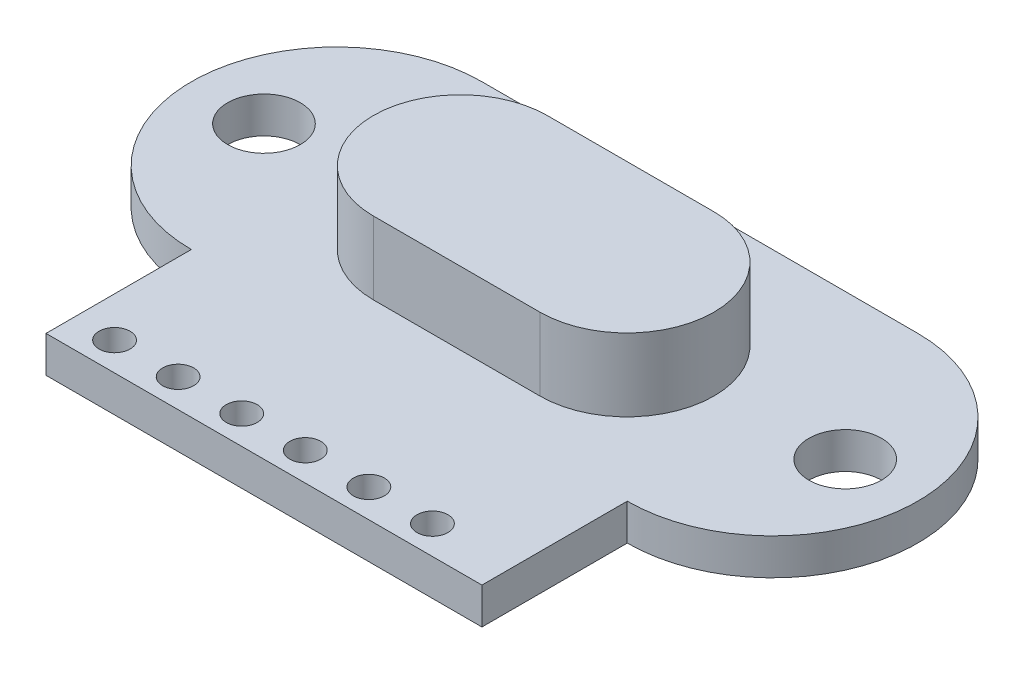
SolidWorks part; units mm, degrees
ref_plane "Front Plane" through (0, 0, 0) normal (0, 0, 1) x (1, 0, 0)
ref_plane "Top Plane" through (0, 0, 0) normal (0, 1, 0) x (1, 0, 0)
ref_plane "Right Plane" through (0, 0, 0) normal (1, 0, 0) x (0, 0, -1)
sketch "Sketch1" plane through (0, 0, 0) normal (0, 1, 0) x (1, 0, 0)
  line L0 (-6, 8) -> (6, 8) construction
  line L1 (-6, 12) -> (6, 12)
  line L2 (-6, 4) -> (6, 4)
  line L3 (0, 8) -> (0, 0) construction
  arc A0 (-6, 12) -> (-6, 4) centre (-6, 8) ccw
  arc A1 (6, 4) -> (6, 12) centre (6, 8) ccw
  point P2 (0, 8)
  dimension "D2" = 20
  dimension "D1" = 12
  dimension "D3" = 8
extrude "Boss-Extrude1" add sketch "Sketch1" along normal blind 1
sketch "Sketch2" plane through (0, 0, 0) normal (0, -1, 0) x (1, 0, 0)
  line L1 (-6, -4) -> (6, -4)
  line L2 (-6, -4) -> (-6, 0)
  line L3 (-6, 0) -> (6, 0)
  line L4 (6, -4) -> (6, 0)
extrude "Boss-Extrude2" add sketch "Sketch2" against normal blind 1
sketch "Sketch3" plane through (0, 1, 0) normal (0, 1, 0) x (1, 0, 0)
  line L0 (-8, 8) -> (8, 8) construction
  line L1 (0, 4) -> (0, 8) construction
  circle A0 centre (8, 8) radius 1
  circle A1 centre (-8, 8) radius 1
  circle A2 centre (-4.8957, 0.7833) radius 0.4268
  circle A8 centre (-3.1457, 0.7833) radius 0.4268
  circle A9 centre (-1.3957, 0.7833) radius 0.4268
  circle A10 centre (0.3543, 0.7833) radius 0.4268
  circle A11 centre (2.1043, 0.7833) radius 0.4268
  circle A12 centre (3.8543, 0.7833) radius 0.4268
  dimension "D1" = 2
  dimension "D4" = 6
  dimension "D2" = 4
  dimension "D3" = 16
extrude "Cut-Extrude1" cut sketch "Sketch3" against normal through all
sketch "Sketch4" plane through (0, 1, 0) normal (0, 1, 0) x (1, 0, 0)
  line L0 (-2.294, 7.6988) -> (2.294, 7.6988) construction
  line L1 (-2.294, 10.0931) -> (2.294, 10.0931)
  line L2 (-2.294, 5.3044) -> (2.294, 5.3044)
  line L3 (0, 7.6988) -> (0, 0) construction
  arc A0 (-2.294, 10.0931) -> (-2.294, 5.3044) centre (-2.294, 7.6988) ccw
  arc A1 (2.294, 5.3044) -> (2.294, 10.0931) centre (2.294, 7.6988) ccw
  point P2 (0, 7.6988)
extrude "Boss-Extrude3" add sketch "Sketch4" along normal blind 2
sketch "Sketch5" plane through (0, 0, 0) normal (0, -1, 0) x (1, 0, 0)
  line L1 (-4.4007, -4.2879) -> (4.1466, -4.2879)
  line L2 (-4.4007, -4.2879) -> (-4.4007, -9.6116)
  line L3 (-4.4007, -9.6116) -> (4.1466, -9.6116)
  line L4 (4.1466, -4.2879) -> (4.1466, -9.6116)
extrude "Boss-Extrude4" add sketch "Sketch5" along normal blind 1
